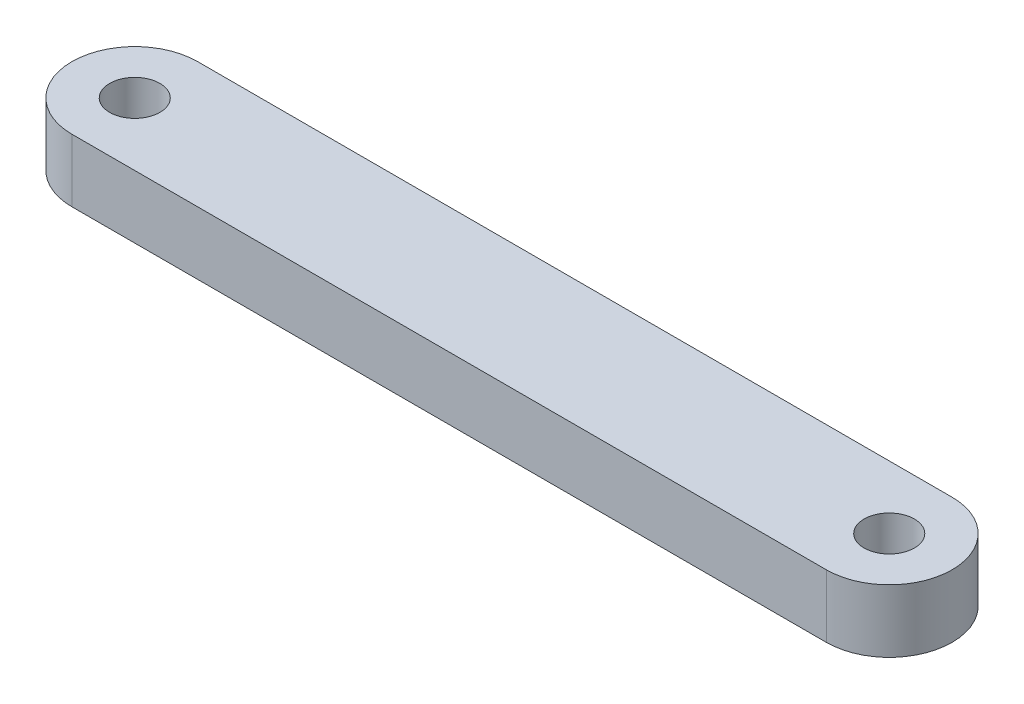
SolidWorks part; units mm, degrees
ref_plane "Alzado" through (0, 0, 0) normal (0, 0, 1) x (1, 0, 0)
ref_plane "Planta" through (0, 0, 0) normal (0, 1, 0) x (1, 0, 0)
ref_plane "Vista lateral" through (0, 0, 0) normal (1, 0, 0) x (0, 0, -1)
sketch "Croquis1" plane through (0, 0, 0) normal (0, 1, 0) x (1, 0, 0)
  line L0 (0, 0) -> (60, 0) construction
  line L1 (0, 5) -> (60, 5)
  line L2 (0, -5) -> (60, -5)
  arc A0 (0, 5) -> (0, -5) centre (0, 0) ccw
  arc A1 (60, -5) -> (60, 5) centre (60, 0) ccw
  circle A2 centre (0, 0) radius 2
  circle A3 centre (60, 0) radius 2
  point P3 (30, 0)
  dimension "D2" = 5
  dimension "D3" = 4
  dimension "D1" = 60
extrude "Saliente-Extruir1" add sketch "Croquis1" along normal blind 5
